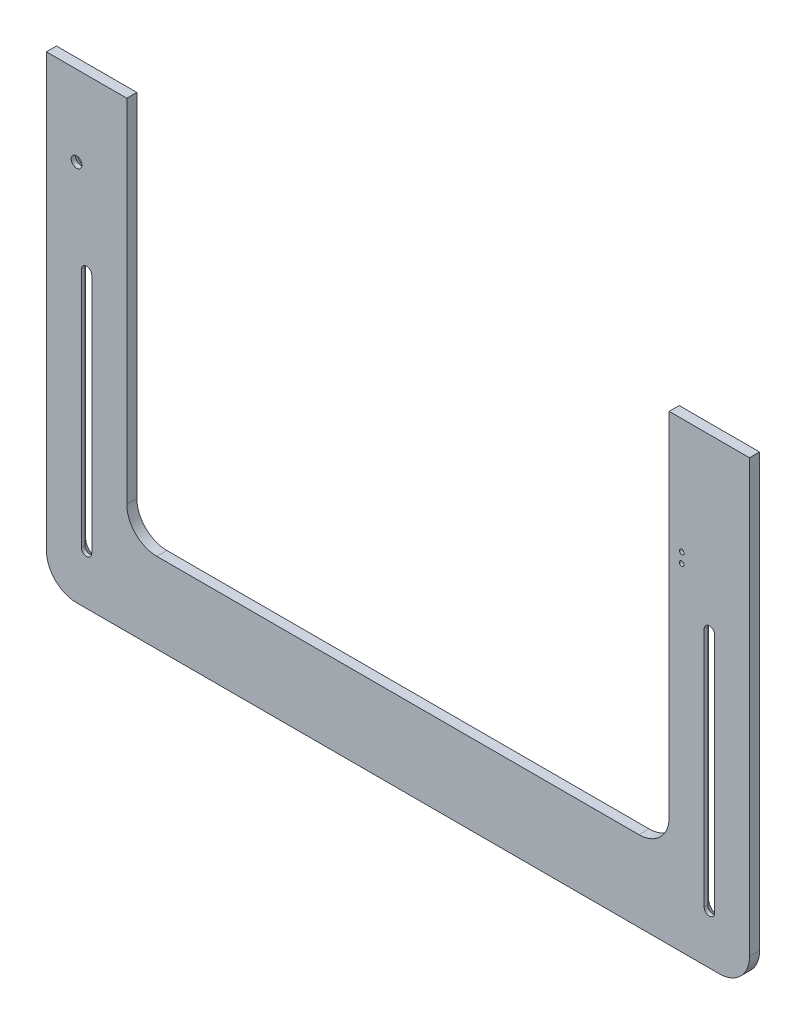
SolidWorks part; units mm, degrees
ref_plane "Front Plane" through (0, 0, 0) normal (0, 0, 1) x (1, 0, 0)
ref_plane "Top Plane" through (0, 0, 0) normal (0, 1, 0) x (1, 0, 0)
ref_plane "Right Plane" through (0, 0, 0) normal (1, 0, 0) x (0, 0, -1)
sketch "Sketch1" plane through (0, 0, 0) normal (0, 0, 1) x (1, 0, 0)
  line L0 (0, 0) -> (0, -292.1)
  line L1 (0, -292.1) -> (444.5, -292.1)
  line L2 (444.5, -292.1) -> (444.5, 0)
  line L3 (444.5, 0) -> (393.7, 0)
  line L4 (393.7, 0) -> (393.7, -241.3)
  line L5 (393.7, -241.3) -> (50.8, -241.3)
  line L6 (50.8, -241.3) -> (50.8, 0)
  line L7 (50.8, 0) -> (0, 0)
  dimension "D1" = 292.1
  dimension "D2" = 444.5
  dimension "D3" = 50.8
  dimension "D4" = 50.8
  dimension "D5" = 241.3
extrude "Boss-Extrude1" add sketch "Sketch1" along normal blind 6.35
fillet "Fillet5" radius 19.05 1 edges at (0, -292.1, 3.175)
fillet "Fillet6" radius 19.05 1 edges at (444.5, -292.1, 3.175)
fillet "Fillet7" radius 19.05 1 edges at (50.8, -241.3, 3.175)
fillet "Fillet8" radius 19.05 1 edges at (393.7, -241.3, 3.175)
sketch "Sketch2" plane through (0, 0, 6.35) normal (0, 0, 1) x (1, 0, 0)
  line L0 (25.4, -260.35) -> (25.4, -107.95) construction
  line L1 (22.1361, -260.35) -> (22.1361, -107.95)
  line L2 (28.6639, -260.35) -> (28.6639, -107.95)
  line L3 (374.65, -241.3) -> (69.85, -241.3) construction
  line L4 (0, 0) -> (0, -273.05) construction
  arc A0 (22.1361, -260.35) -> (28.6639, -260.35) centre (25.4, -260.35) ccw
  arc A1 (28.6639, -107.95) -> (22.1361, -107.95) centre (25.4, -107.95) ccw
  point P2 (25.4, -184.15)
  dimension "D1" = 19.05
  dimension "D2" = 25.4
extrude "Cut-Extrude1" cut sketch "Sketch2" against normal through all contours L2 A1 L1 A0
sketch "Sketch4" plane through (0, 0, 6.35) normal (0, 0, 1) x (1, 0, 0)
  line L0 (419.1, -260.35) -> (419.1, -107.95) construction
  line L1 (415.8361, -260.35) -> (415.8361, -107.95)
  line L2 (422.3639, -260.35) -> (422.3639, -107.95)
  line L3 (444.5, -273.05) -> (444.5, 0) construction
  line L4 (374.65, -241.3) -> (69.85, -241.3) construction
  arc A0 (415.8361, -260.35) -> (422.3639, -260.35) centre (419.1, -260.35) ccw
  arc A1 (422.3639, -107.95) -> (415.8361, -107.95) centre (419.1, -107.95) ccw
  point P2 (419.1, -184.15)
  dimension "D1" = 25.4
  dimension "D2" = 19.05
extrude "Cut-Extrude2" cut sketch "Sketch4" against normal through all
hole_wizard "CSK for 1/4 Flat Head Machine Screw2" positions "Sketch11" profile "Sketch10" countersink size "1/4" standard "ANSI Inch" end condition through all
sketch "Sketch11" plane through (0, 0, 0) normal (0, 0, -1) x (-1, 0, 0)
  point P0 (-19.05, -50.8)
sketch "Sketch10" plane through (19.05, -50.8, 0) normal (1, 0, 0) x (0, 1, 0)
  line L0 (0, 0) -> (0, 6.35)
  line L1 (0, 6.35) -> (3.3782, 6.35)
  line L2 (3.3782, 6.35) -> (3.3782, 3.5209)
  line L3 (3.3782, 3.5209) -> (6.4389, 0)
  line L5 (6.4389, 0) -> (0, 0)
  line L6 (-3.3782, 3.5209) -> (-6.4389, 0) construction
  line L11 (0, -6.35) -> (0, 107.95) construction
  dimension "Thru Hole Dia." = 6.7564
  dimension "Thru Hole Depth" = 6.35
  dimension "Near C'Sink Dia." = 12.8778
  dimension "Near C'Sink Angle" = 82
chamfer "Chamfer1" distance 4.0894 angle 42 4 edges at (419.1, -104.6861, 0) (415.8361, -184.15, 0) (419.1, -263.6139, 0) (422.3639, -184.15, 0)
chamfer "Chamfer2" distance 4.0894 angle 42 4 edges at (25.4, -104.6861, 0) (22.1361, -184.15, 0) (25.4, -263.6139, 0) (28.6639, -184.15, 0)
ref_plane "Plane1" through (222.25, 0, 0) normal (1, 0, 0) x (0, 0, -1)
hole_wizard "#32 (0.116) Diameter Hole1" positions "Sketch24" profile "Sketch23" hole size "#32" standard "ANSI Inch"
sketch "Sketch24" plane through (0, 0, 6.35) normal (0, 0, 1) x (1, 0, 0)
  point P0 (401.6375, -73.025)
  point P3 (401.6375, -79.375)
sketch "Sketch23" plane through (401.6375, -73.025, 6.35) normal (1, 0, 0) x (0, -1, 0)
  line L0 (0, 0) -> (0, 26.2852)
  line L1 (0, 26.2852) -> (1.4732, 25.4)
  line L2 (1.4732, 25.4) -> (1.4732, 0)
  line L5 (1.4732, 0) -> (0, 0)
  line L10 (0, 26.2852) -> (-1.4732, 25.4) construction
  line L11 (0, -6.35) -> (0, 107.95) construction
  dimension "Hole Dia." = 2.9464
  dimension "Hole Depth" = 25.4
  dimension "Drill Angle" = 118
